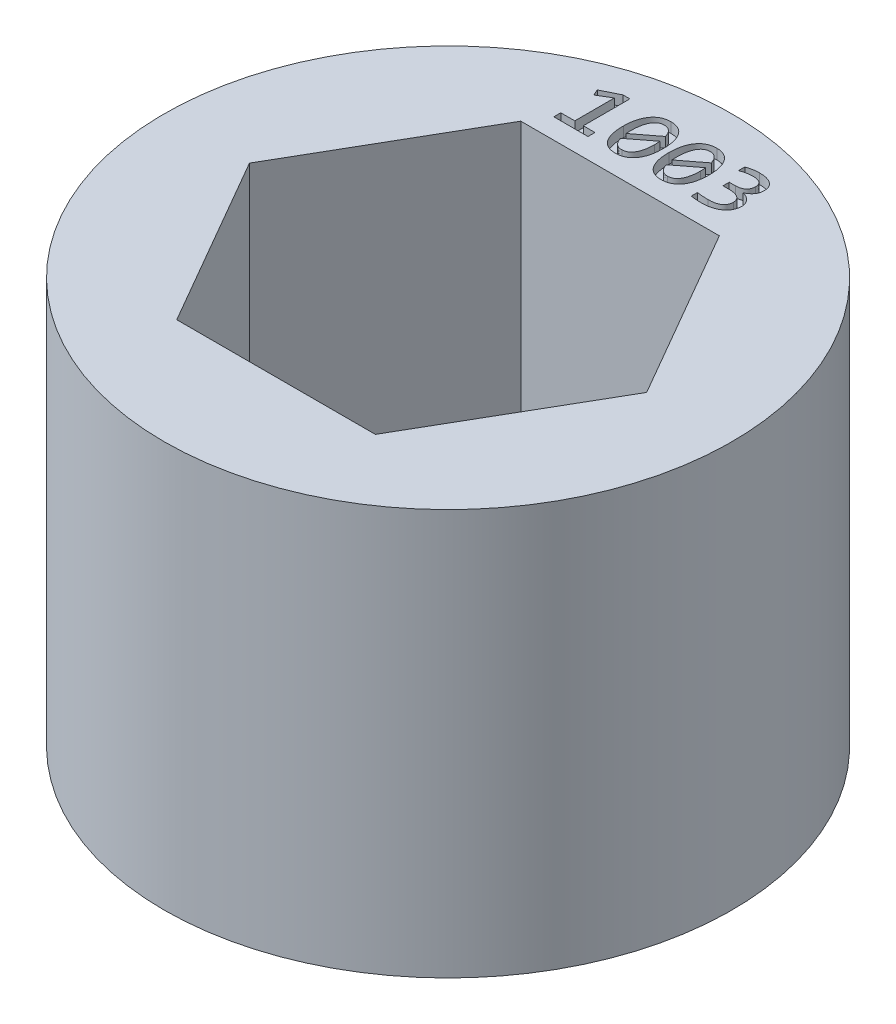
SolidWorks part; units mm, degrees
material "Nylon 101"
ref_plane "Front Plane" through (0, 0, 0) normal (0, 0, 1) x (1, 0, 0)
ref_plane "Top Plane" through (0, 0, 0) normal (0, 1, 0) x (1, 0, 0)
ref_plane "Right Plane" through (0, 0, 0) normal (1, 0, 0) x (0, 0, -1)
sketch "Sketch1" plane through (0, 0, 0) normal (0, 1, 0) x (1, 0, 0)
  line L1 (7.7723, 0) -> (3.8861, 6.731)
  line L2 (3.8861, 6.731) -> (-3.8861, 6.731)
  line L3 (-3.8861, 6.731) -> (-7.7723, 0)
  line L4 (-7.7723, 0) -> (-3.8861, -6.731)
  line L5 (-3.8861, -6.731) -> (3.8861, -6.731)
  line L6 (3.8861, -6.731) -> (7.7723, 0)
  circle A0 centre (0, 0) radius 6.731 construction
  circle A1 centre (0, 0) radius 11.1125
  dimension "D1" = 13.462
  dimension "D2" = 22.225
extrude "Boss-Extrude1" add sketch "Sketch1" along normal blind 15.875
sketch "Sketch2" plane through (0, 15.875, 0) normal (0, 1, 0) x (1, 0, 0)
  line L0 (-4.2615, 7.5247) -> (4.1119, 7.5247) construction
  line L1 (3.8861, 6.731) -> (-3.8861, 6.731) construction
  text T0 "1003" font "Consolas" height in points 8
  dimension "D1" = 0.7937
extrude "Cut-Extrude1" cut sketch "Sketch2" against normal blind 0.4
